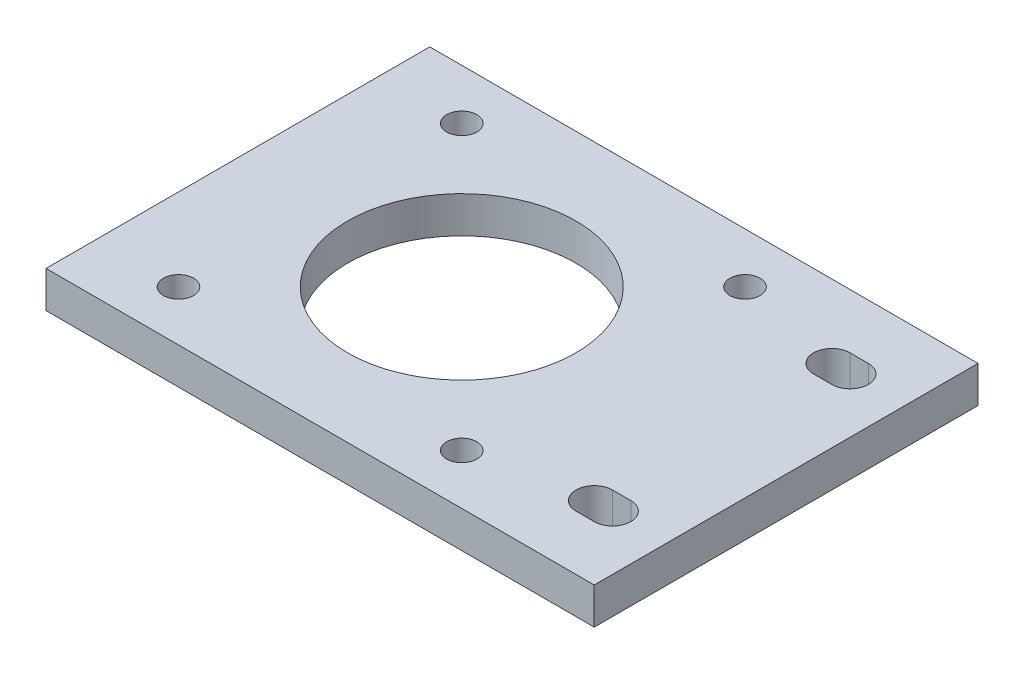
SolidWorks part; units mm, degrees
ref_plane "前视基准面" through (0, 0, 0) normal (0, 0, 1) x (1, 0, 0)
ref_plane "上视基准面" through (0, 0, 0) normal (0, 1, 0) x (1, 0, 0)
ref_plane "右视基准面" through (0, 0, 0) normal (1, 0, 0) x (0, 0, -1)
sketch "草图1" plane through (0, 0, 0) normal (0, 1, 0) x (1, 0, 0)
  line L0 (45.2479, -4.103) -> (47.2479, -4.103) construction
  line L1 (-6.7521, 3.897) -> (53.2479, 3.897)
  line L2 (-6.7521, 3.897) -> (-6.7521, -38.103)
  line L3 (-6.7521, -38.103) -> (53.2479, -38.103)
  line L4 (53.2479, 3.897) -> (53.2479, -38.103)
  line L5 (-6.7521, 3.897) -> (53.2479, -38.103) construction
  line L6 (-6.7521, -38.103) -> (53.2479, 3.897) construction
  line L7 (45.2479, -2.103) -> (47.2479, -2.103)
  line L8 (45.2479, -6.103) -> (47.2479, -6.103)
  line L9 (53.2479, -17.103) -> (-6.7521, -17.103) construction
  line L10 (45.2479, -30.103) -> (47.2479, -30.103) construction
  line L11 (45.2479, -32.103) -> (47.2479, -32.103)
  line L12 (45.2479, -28.103) -> (47.2479, -28.103)
  line L14 (2.2479, -1.603) -> (33.2479, -1.603) construction
  line L15 (2.2479, -1.603) -> (2.2479, -32.603) construction
  line L16 (2.2479, -32.603) -> (33.2479, -32.603) construction
  line L17 (33.2479, -1.603) -> (33.2479, -32.603) construction
  line L18 (17.7479, -32.603) -> (17.7479, -1.603) construction
  line L19 (2.2479, -17.103) -> (33.2479, -17.103) construction
  arc A0 (45.2479, -2.103) -> (45.2479, -6.103) centre (45.2479, -4.103) ccw
  arc A1 (47.2479, -6.103) -> (47.2479, -2.103) centre (47.2479, -4.103) ccw
  arc A2 (45.2479, -32.103) -> (45.2479, -28.103) centre (45.2479, -30.103) cw
  arc A3 (47.2479, -28.103) -> (47.2479, -32.103) centre (47.2479, -30.103) cw
  circle A4 centre (2.2479, -1.603) radius 1.65
  circle A5 centre (33.2479, -1.603) radius 1.65
  circle A6 centre (33.2479, -32.603) radius 1.65
  circle A7 centre (2.2479, -32.603) radius 1.65
  circle A8 centre (17.7479, -17.103) radius 12.5
  point P4 (23.2479, -17.103)
  point P7 (46.2479, -4.103)
  point P16 (46.2479, -30.103)
  point P21 (17.7479, -17.103)
  dimension "D5" = 6
  dimension "D7" = 12
  dimension "D10" = 25
  dimension "D11" = 3.3
  dimension "D1" = 42
  dimension "D2" = 60
  dimension "D3" = 4
  dimension "D4" = 2
  dimension "D6" = 6
  dimension "D8" = 31
  dimension "D9" = 31
extrude "凸台-拉伸1" add sketch "草图1" along normal blind 4
